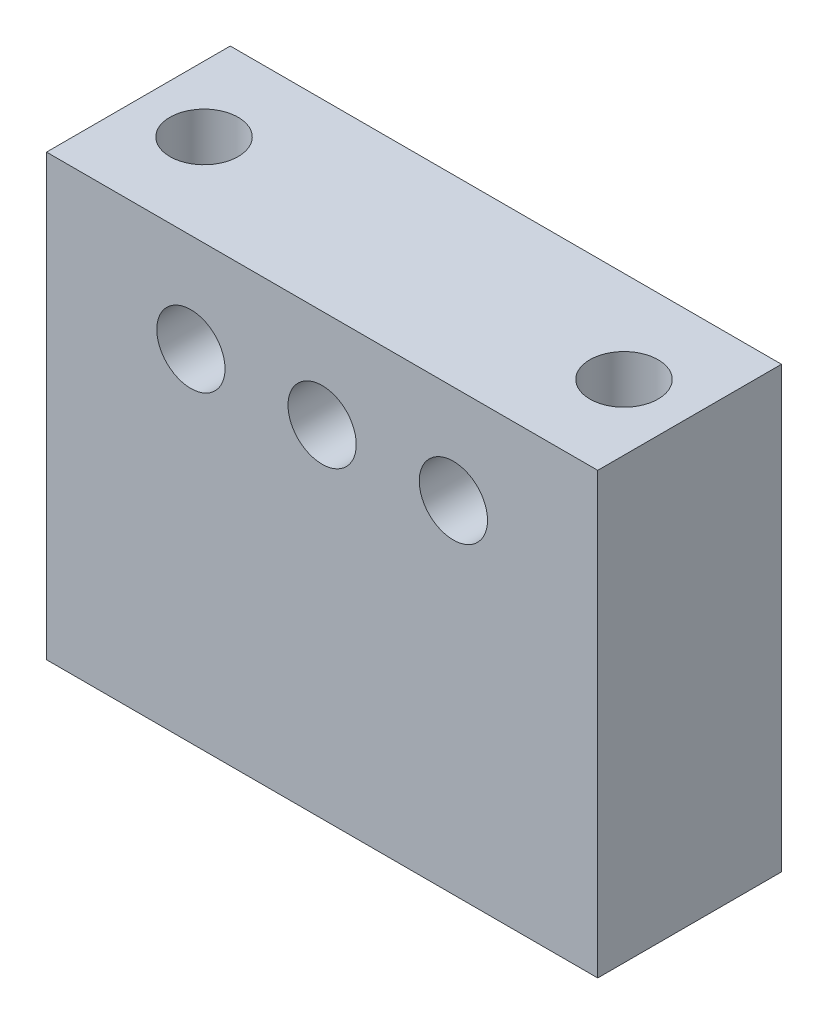
SolidWorks part; units mm, degrees
ref_plane "Front Plane" through (0, 0, 0) normal (0, 0, 1) x (1, 0, 0)
ref_plane "Top Plane" through (0, 0, 0) normal (0, 1, 0) x (1, 0, 0)
ref_plane "Right Plane" through (0, 0, 0) normal (1, 0, 0) x (0, 0, -1)
sketch "Sketch3" plane through (0, 0, 0) normal (0, 1, 0) x (1, 0, 0)
  line L1 (-21, -7) -> (21, -7)
  line L2 (-21, -7) -> (-21, 7)
  line L3 (-21, 7) -> (21, 7)
  line L4 (21, -7) -> (21, 7)
  line L5 (-21, -7) -> (21, 7) construction
  line L6 (-21, 7) -> (21, -7) construction
  point P0 (0, 0)
  dimension "D1" = 14
  dimension "D2" = 42
extrude "Boss-Extrude2" add sketch "Sketch3" along normal blind 33.5
sketch "Sketch4" plane through (0, 33.5, 0) normal (0, 1, 0) x (1, 0, 0)
  line L0 (-1000, 0) -> (49000, 0) construction
  circle A0 centre (-16, 0) radius 2.6
  circle A1 centre (16, 0) radius 2.6
  dimension "D1" = 32
  dimension "D2" = 16
  dimension "D3" = 5.2
  dimension "D4" = 5.2
extrude "Cut-Extrude2" cut sketch "Sketch4" against normal through all
sketch "Sketch5" plane through (0, 0, 7) normal (0, 0, 1) x (1, 0, 0)
  line L0 (-1010.7927, 26) -> (48989.2073, 26) construction
  line L1 (-21, 33.5) -> (21, 33.5) construction
  circle A0 centre (0, 26) radius 2.6
  circle A1 centre (10, 26) radius 2.6
  circle A2 centre (-10, 26) radius 2.6
  dimension "D2" = 5.2
  dimension "D3" = 5.2
  dimension "D4" = 5.2
  dimension "D5" = 10
  dimension "D6" = 10
  dimension "D1" = 7.5
extrude "Cut-Extrude3" cut sketch "Sketch5" against normal through all
